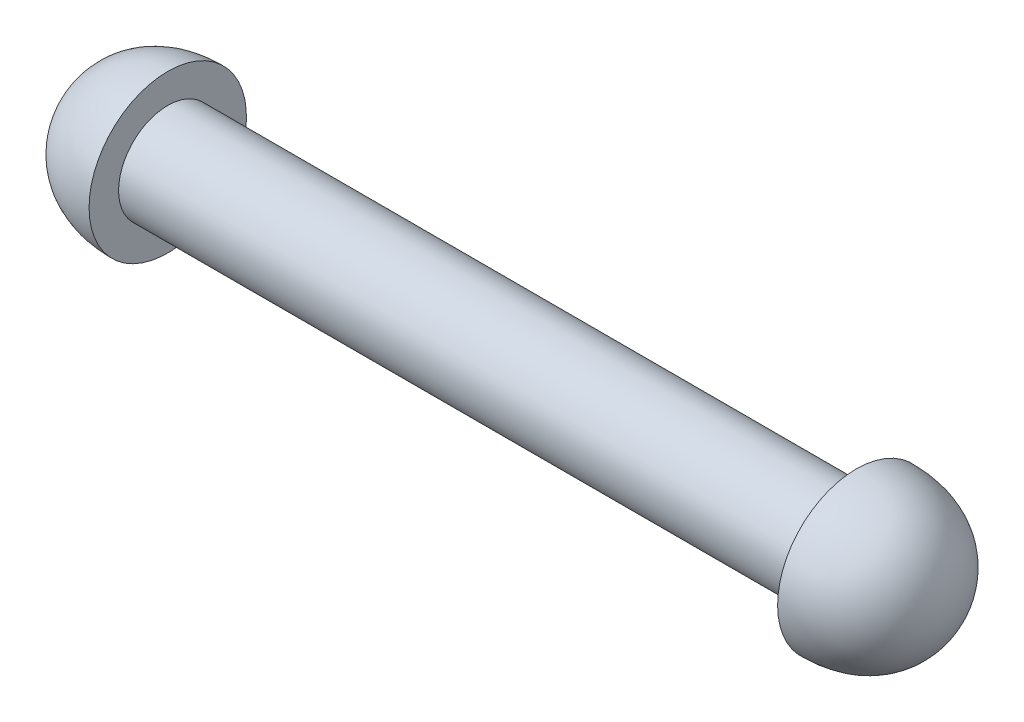
SolidWorks part; units mm, degrees
ref_plane "Front Plane" through (0, 0, 0) normal (0, 0, 1) x (1, 0, 0)
ref_plane "Top Plane" through (0, 0, 0) normal (0, 1, 0) x (1, 0, 0)
ref_plane "Right Plane" through (0, 0, 0) normal (1, 0, 0) x (0, 0, -1)
sketch "Sketch1" plane through (0, 0, 0) normal (1, 0, 0) x (0, 0, -1)
  circle A0 centre (0, 0) radius 25
  dimension "D1" = 50
extrude "Boss-Extrude1" add sketch "Sketch1" along normal blind 175
sketch "Sketch3" plane through (0, 0, 0) normal (0, 0, 1) x (1, 0, 0)
  line L2 (-100.0787, 0) -> (83.5342, 0) construction
  line L3 (0, 0) -> (-45.4584, 0)
  line L4 (0, 40) -> (0, 0)
  spline S0 degree 3 poles (-45.4584, 0) (-45.4584, 20.1838) (-30.9912, 40) (0, 40) knots 0 0 0 0 1 1 1 1
  dimension "D1" = 40
revolve "Revolve1" add sketch "Sketch3" angle 360 about L2
mirror "Mirror1" about plane through (175, 0, 0) normal (1, 0, 0) of "Boss-Extrude1", "Revolve1"
